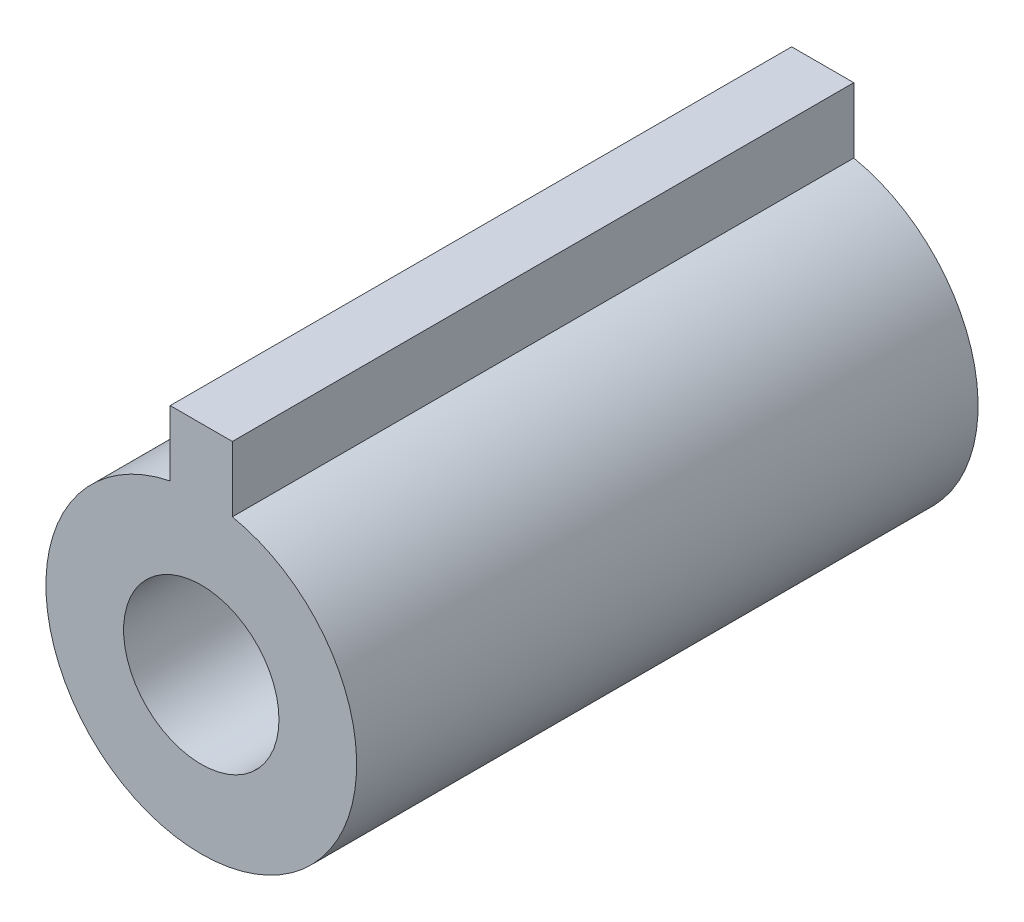
SolidWorks part; units mm, degrees
ref_plane "Front Plane" through (0, 0, 0) normal (0, 0, 1) x (1, 0, 0)
ref_plane "Top Plane" through (0, 0, 0) normal (0, 1, 0) x (1, 0, 0)
ref_plane "Right Plane" through (0, 0, 0) normal (1, 0, 0) x (0, 0, -1)
sketch "Sketch2" plane through (0, 0, 0) normal (0, 0, 1) x (1, 0, 0)
  line L0 (0, 0) -> (0, 7) construction
  line L1 (1, 4.899) -> (1, 7)
  line L2 (1, 7) -> (-1, 7)
  line L3 (-1, 7) -> (-1, 4.899)
  circle A0 centre (0, 0) radius 2.5
  arc A1 (-1, 4.899) -> (1, 4.899) centre (0, 0) ccw
  point P3 (0, 0)
  point P8 (0, 0)
  dimension "D1" = 5
  dimension "D2" = 10
  dimension "D3" = 2
  dimension "D4" = 7
extrude "Boss-Extrude1" add sketch "Sketch2" along normal blind 20
